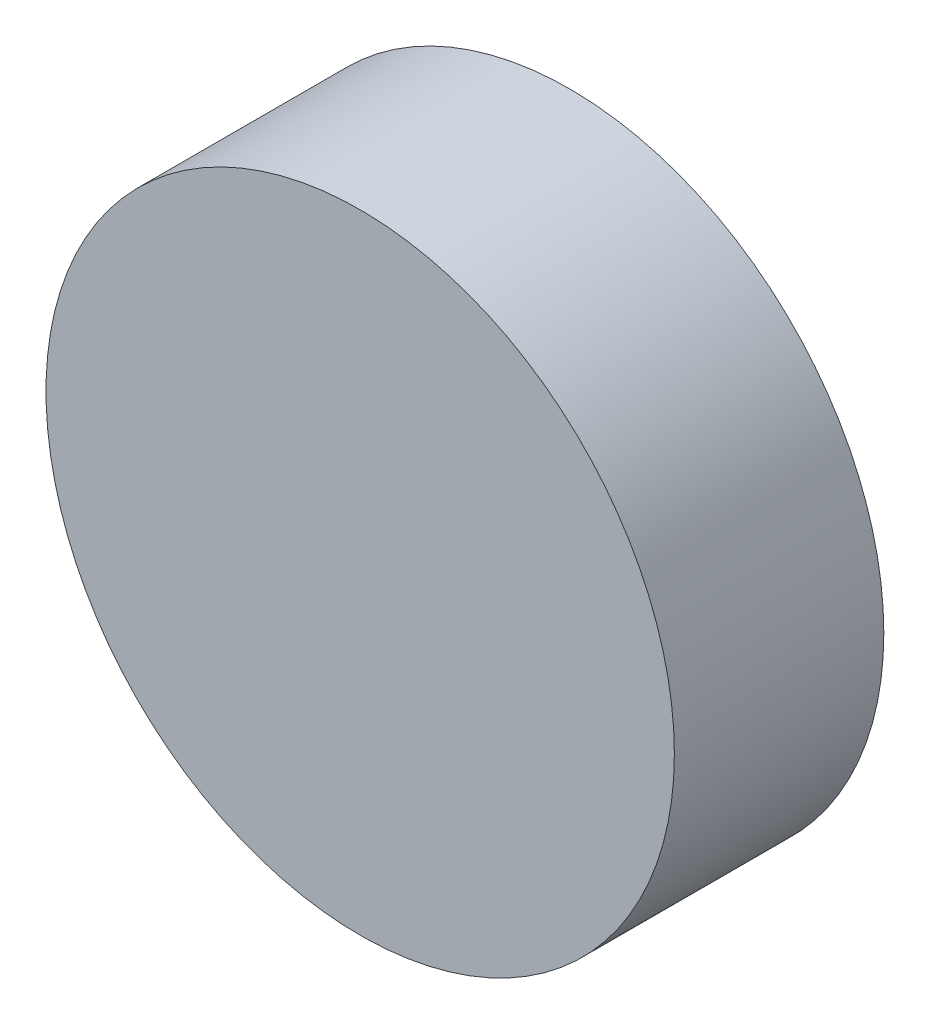
SolidWorks part; units mm, degrees
ref_plane "前视基准面" through (0, 0, 0) normal (0, 0, 1) x (1, 0, 0)
ref_plane "上视基准面" through (0, 0, 0) normal (0, 1, 0) x (1, 0, 0)
ref_plane "右视基准面" through (0, 0, 0) normal (1, 0, 0) x (0, 0, -1)
other "Configuration Table"
sketch "草图1" plane through (0, 0, 0) normal (0, 0, 1) x (1, 0, 0)
  circle A0 centre (0, 0) radius 12
extrude "凸台-拉伸1" add sketch "草图1" along normal mid plane 8
